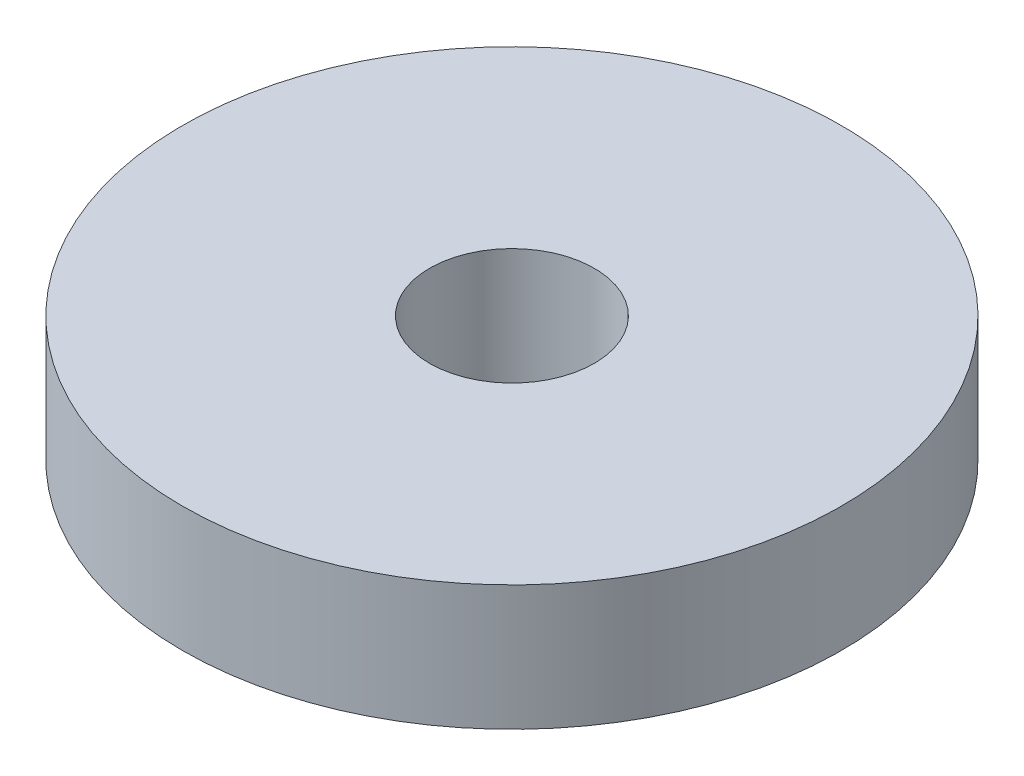
SolidWorks part; units mm, degrees
ref_plane "Front" through (0, 0, 0) normal (0, 0, 1) x (1, 0, 0)
ref_plane "Top" through (0, 0, 0) normal (0, 1, 0) x (1, 0, 0)
ref_plane "Right" through (0, 0, 0) normal (1, 0, 0) x (0, 0, -1)
sketch "Sketch1" plane through (0, 0, 0) normal (0, 1, 0) x (1, 0, 0)
  circle A0 centre (0, 0) radius 6.35
  circle A1 centre (0, 0) radius 1.5875
  dimension "D1" = 3.175
  dimension "D2" = 12.7
extrude "Boss-Extrude1" add sketch "Sketch1" along normal blind 2.41
